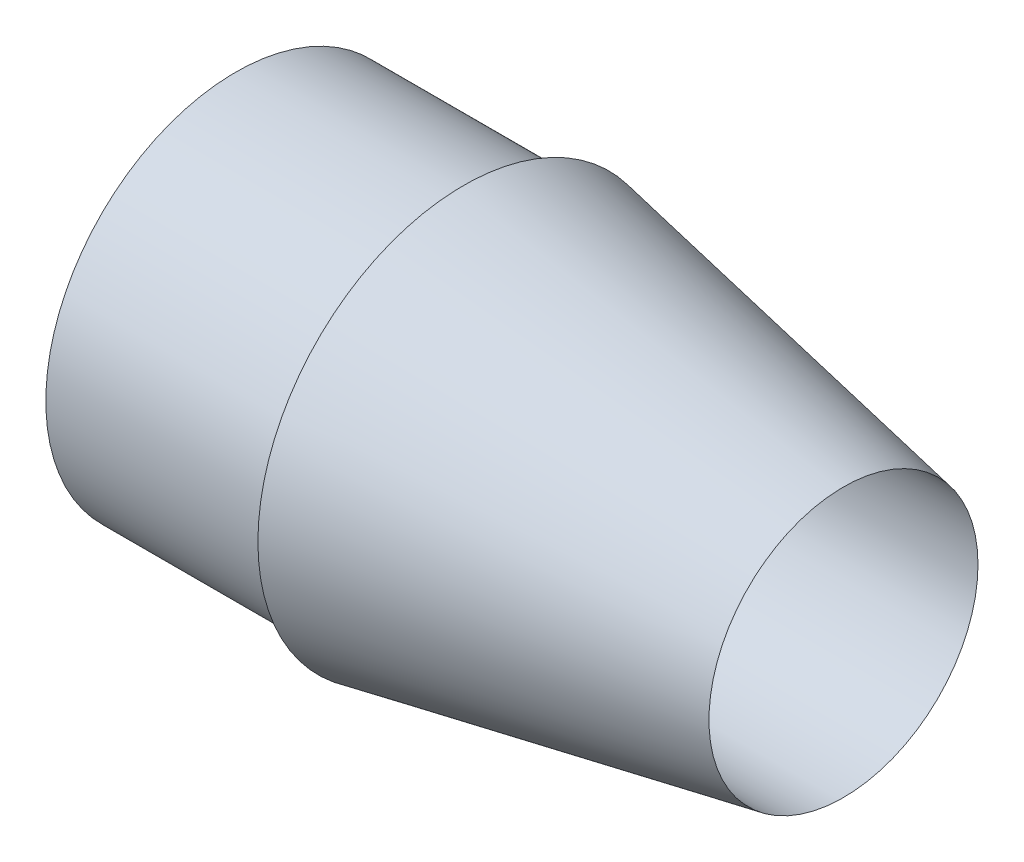
SolidWorks part; units mm, degrees
ref_plane "Front Plane" through (0, 0, 0) normal (0, 0, 1) x (1, 0, 0)
ref_plane "Top Plane" through (0, 0, 0) normal (0, 1, 0) x (1, 0, 0)
ref_plane "Right Plane" through (0, 0, 0) normal (1, 0, 0) x (0, 0, -1)
sketch "Sketch2" plane through (0, 0, 0) normal (0, 0, 1) x (1, 0, 0)
  line L0 (0, 26.9875) -> (76.2, 26.9875)
  line L1 (76.2, 26.9875) -> (0, 41.275)
  line L2 (0, 41.275) -> (0, 38.1)
  line L3 (0, 38.1) -> (-45.72, 38.1)
  line L6 (0, 25.4) -> (0, 26.9875)
  line L8 (-2.6655, 25.6829) -> (-45.72, 34.925)
  line L9 (-45.72, 38.1) -> (-45.72, 34.925)
  arc A0 (0, 25.4) -> (-2.6655, 25.6829) centre (0, 38.1) cw
  dimension "D1" = 76.2
  dimension "D2" = 26.9875
  dimension "D3" = 41.275
  dimension "D4" = 38.1
  dimension "D5" = 45.72
  dimension "D6" = 25.4
  dimension "D7" = 3.175
ref_axis "Axis1" through (109.22, 0, 0) along (-1, 0, 0)
revolve "Revolve1" add sketch "Sketch2" angle 360 about axis through (109.22, 0, 0) along (-1, 0, 0)
